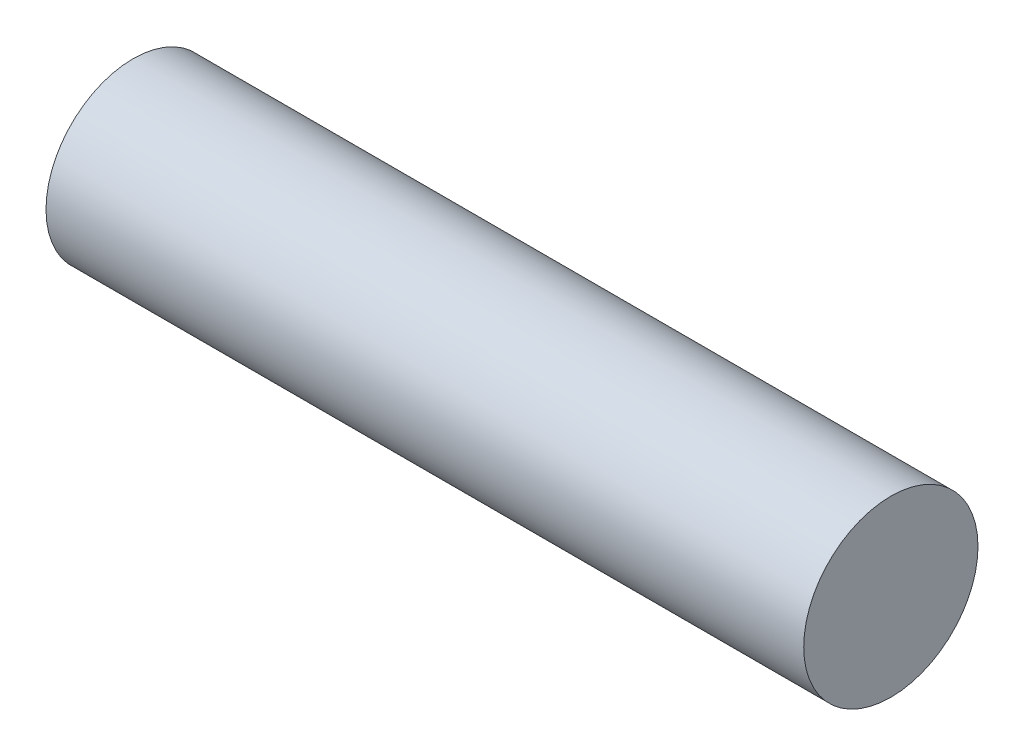
SolidWorks part; units mm, degrees
ref_plane "Front Plane" through (0, 0, 0) normal (0, 0, 1) x (1, 0, 0)
ref_plane "Top Plane" through (0, 0, 0) normal (0, 1, 0) x (1, 0, 0)
ref_plane "Right Plane" through (0, 0, 0) normal (1, 0, 0) x (0, 0, -1)
sketch "Sketch1" plane through (0, 0, 0) normal (1, 0, 0) x (0, 0, -1)
  circle A0 centre (0, 0) radius 1.4605
  dimension "D1" = 2.921
extrude "Boss-Extrude1" add sketch "Sketch1" along normal blind 12.7
